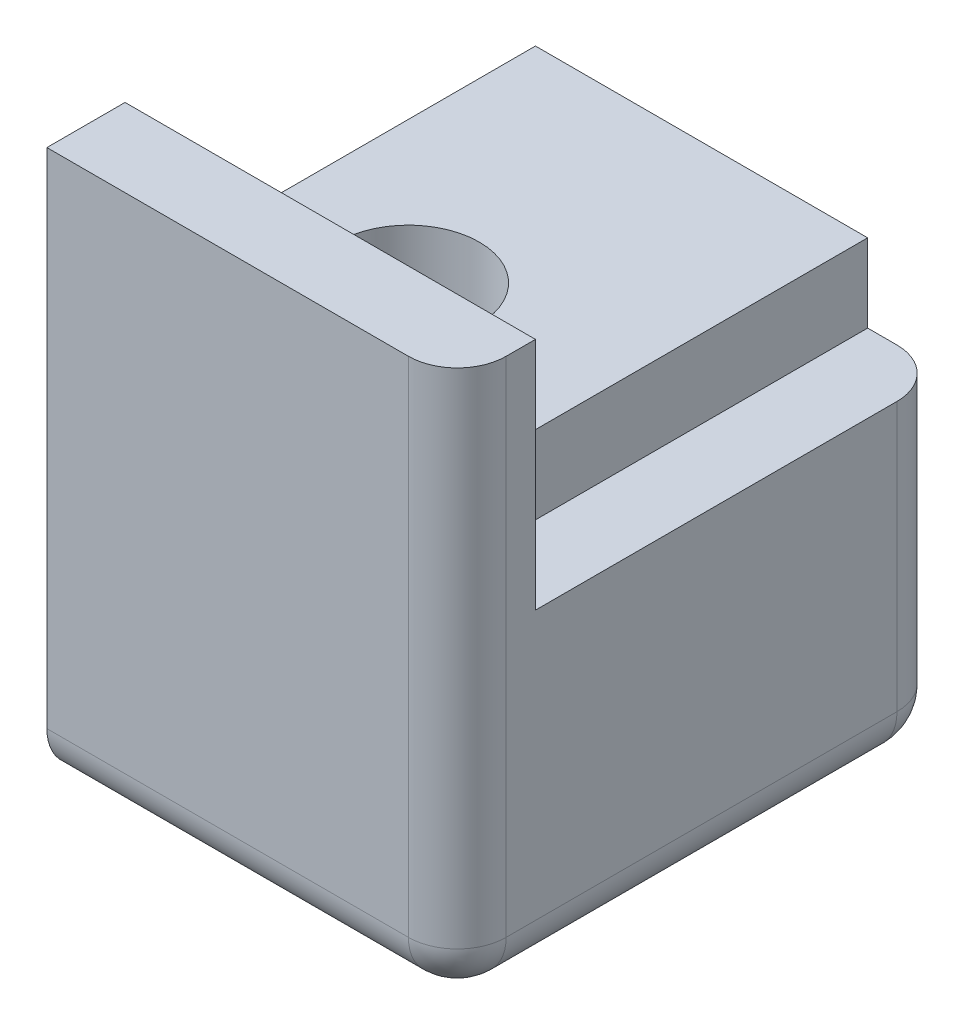
SolidWorks part; units mm, degrees
ref_plane "Front Plane" through (0, 0, 0) normal (0, 0, 1) x (1, 0, 0)
ref_plane "Top Plane" through (0, 0, 0) normal (0, 1, 0) x (1, 0, 0)
ref_plane "Right Plane" through (0, 0, 0) normal (1, 0, 0) x (0, 0, -1)
sketch "Sketch2" plane through (0, 0, 0) normal (0, 1, 0) x (1, 0, 0)
  line L1 (-4.2, -5) -> (4.2, -5)
  line L2 (-4.2, -5) -> (-4.2, 5)
  line L3 (-4.2, 5) -> (4.2, 5)
  line L4 (4.2, -5) -> (4.2, 5)
  line L5 (-4.2, -5) -> (4.2, 5) construction
  line L6 (-4.2, 5) -> (4.2, -5) construction
  point P0 (0, 0)
extrude "Boss-Extrude1" add sketch "Sketch2" along normal blind 11.3
sketch "Sketch5" plane through (4.2, 0, 0) normal (1, 0, 0) x (0, 0, -1)
  line L0 (-5, 11.3) -> (-5, 0) construction
  line L1 (5, 11.3) -> (-3.4, 11.3)
  line L2 (5, 11.3) -> (5, 9.8)
  line L3 (5, 9.8) -> (-3.4, 9.8)
  line L4 (-3.4, 11.3) -> (-3.4, 9.8)
  dimension "D1" = 1.6
  dimension "D2" = 1.5
extrude "Cut-Extrude2" cut sketch "Sketch5" against normal blind 11.3
sketch "Sketch7" plane through (0, 0, -5) normal (0, 0, -1) x (-1, 0, 0)
  line L1 (-4.2, 9.8) -> (-2.6, 9.8)
  line L2 (-4.2, 9.8) -> (-4.2, 6.5)
  line L3 (-4.2, 6.5) -> (-2.6, 6.5)
  line L4 (-2.6, 9.8) -> (-2.6, 6.5)
  dimension "D1" = 1.6
  dimension "D2" = 3.3
extrude "Cut-Extrude4" cut sketch "Sketch7" against normal up to vertex (8.4 mm away)
sketch "Sketch9" plane through (2.6, 0, 0) normal (1, 0, 0) x (0, 0, -1)
  line L0 (5, 6.5) -> (5, 9.8) construction
  line L1 (-3.4, 9.8) -> (5, 9.8)
  line L2 (-3.4, 9.8) -> (-3.4, 8.1)
  line L3 (-3.4, 8.1) -> (5, 8.1)
  line L4 (5, 9.8) -> (5, 8.1)
  line L5 (-3.4, 6.5) -> (5, 6.5) construction
  dimension "D1" = 1.6
extrude "Cut-Extrude5" cut sketch "Sketch9" against normal blind 6.8
sketch "Sketch12" plane through (0, 0, 3.4) normal (0, 0, -1) x (-1, 0, 0)
  line L0 (4.2, 11.3) -> (4.2, 8.1) construction
  line L1 (-2.6, 8.1) -> (4.2, 8.1)
  line L2 (-2.6, 8.1) -> (-2.6, 9.7)
  line L3 (-2.6, 9.7) -> (4.2, 9.7)
  line L4 (4.2, 8.1) -> (4.2, 9.7)
extrude "Boss-Extrude3" add sketch "Sketch12" along normal blind 1.6
fillet "Fillet1" radius 1 5 edges at (0, 0, 5) (4.2, 5.65, 5) (4.2, 3.25, -5) (0, 0, -5) (4.2, 0, 0)
hole_wizard "M3.5x0.6 Tapped Hole1" positions "Sketch19" profile "Sketch18" tap size "M3.5x0.6" standard "ANSI Metric" end condition through all
sketch "Sketch19" plane through (0, 0, 0) normal (0, -1, 0) x (-1, 0, 0)
  line L0 (4.2, 4) -> (4.2, -4) construction
  line L1 (4.2, -5) -> (-3.2, -5) construction
  point P0 (1.3, -0.5)
  point P9 (1.1686, -2.2964)
  dimension "D1" = 2.9
  dimension "D2" = 4.5
sketch "Sketch18" plane through (-1.3, 0, 0.5) normal (1, 0, 0) x (0, 0, -1)
  line L0 (0, 0) -> (0, 11.3)
  line L1 (0, 11.3) -> (1.45, 11.3)
  line L2 (1.45, 11.3) -> (1.45, 0)
  line L5 (1.45, 0) -> (0, 0)
  line L11 (0, -6.35) -> (0, 107.95) construction
  dimension "Thru Tap Drill Dia." = 2.9
  dimension "Thru Tap Drill Depth" = 11.3
cosmetic thread "Hole Thread3" parameters "D2"=3.5
sketch "Sketch20" plane through (2.6, 0, 0) normal (1, 0, 0) x (0, 0, -1)
  line L1 (-1.8, 8.1) -> (-3.4, 8.1)
  line L2 (-1.8, 8.1) -> (-1.8, 9.7)
  line L3 (-1.8, 9.7) -> (-3.4, 9.7)
  line L4 (-3.4, 8.1) -> (-3.4, 9.7)
extrude "Cut-Extrude6" cut sketch "Sketch20" against normal blind 6.8
